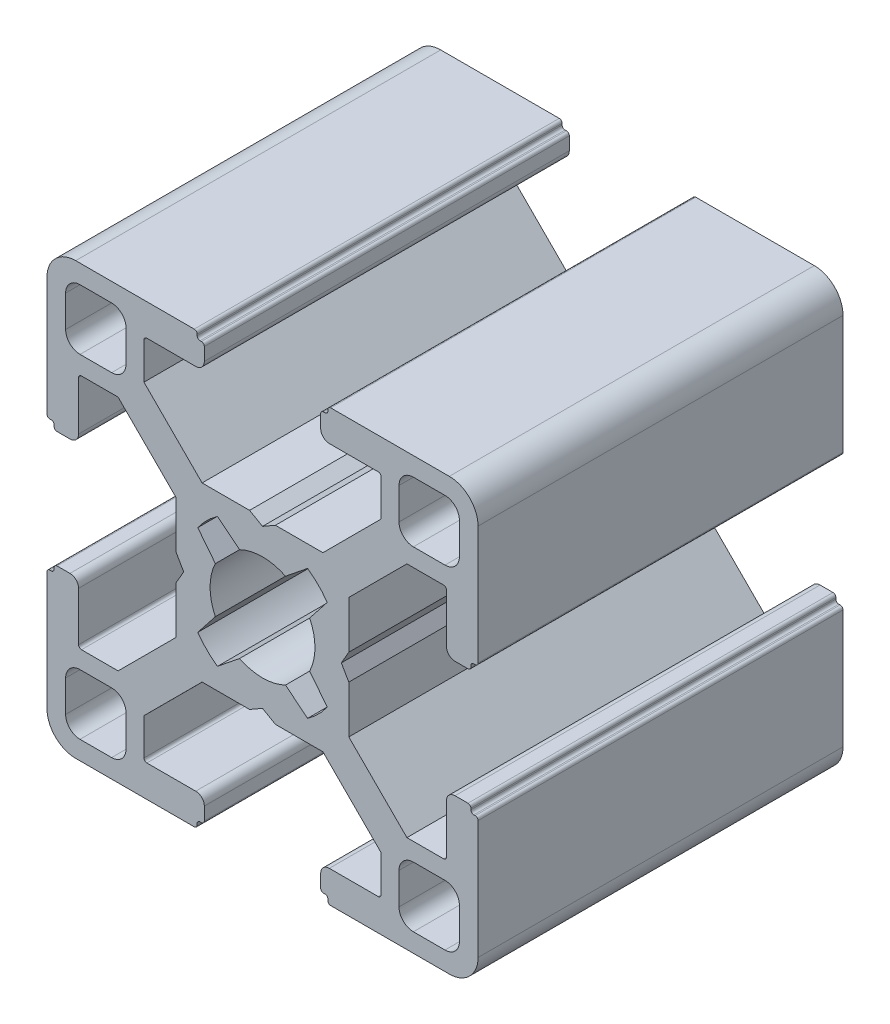
SolidWorks part; units mm, degrees
material "6061 Alloy"
ref_plane "Front" through (0, 0, 0) normal (0, 0, 1) x (1, 0, 0)
ref_plane "Top" through (0, 0, 0) normal (0, 1, 0) x (1, 0, 0)
ref_plane "Right" through (0, 0, 0) normal (1, 0, 0) x (0, 0, -1)
sketch "Sketch1" plane through (0, 0, 0) normal (0, 0, 1) x (1, 0, 0)
  line L0 (13.7, 12.7) -> (13.7, 10.5)
  line L1 (10.5, 9.5) -> (12.7, 9.5)
  line L2 (9.5, 12.7) -> (9.5, 10.5)
  line L3 (10.5, 13.7) -> (12.7, 13.7)
  line L4 (3.1359, 4.5184) -> (1.6001, 3.2806)
  line L5 (3.2806, 1.6001) -> (4.5053, 3.1547)
  line L6 (6.0045, 0.9) -> (5.4849, 0)
  line L7 (6.0045, 4.2045) -> (6.0045, 0.9)
  line L8 (0, -5.4849) -> (0.9, -6)
  line L9 (0.9, -6) -> (4.2045, -6)
  line L10 (4.2045, -6) -> (8.25, -10.05)
  line L11 (8.25, -10.05) -> (8.25, -12.6)
  line L12 (4.65, -12.8) -> (8.05, -12.8)
  line L13 (4.05, -14.3) -> (4.05, -13.4)
  line L14 (4.25, -14.5) -> (4.35, -14.5)
  line L15 (4.55, -14.8) -> (4.55, -14.7)
  line L16 (4.75, -15) -> (13, -15)
  line L17 (15, -13) -> (15, -4.75)
  line L18 (14.7, -4.55) -> (14.8, -4.55)
  line L19 (14.5, -4.35) -> (14.5, -4.25)
  line L20 (13.4, -4.05) -> (14.3, -4.05)
  line L21 (12.8, -8.05) -> (12.8, -4.65)
  line L22 (12.6, -8.25) -> (10.05, -8.25)
  line L23 (10.05, -8.25) -> (6.0045, -4.2045)
  line L24 (6.0045, -4.2045) -> (6.0045, -0.9)
  line L25 (6.0045, -0.9) -> (5.4849, 0)
  line L26 (10.05, 8.25) -> (6.0045, 4.2045)
  line L27 (12.6, 8.25) -> (10.05, 8.25)
  line L28 (12.8, 8.05) -> (12.8, 4.65)
  line L29 (13.4, 4.05) -> (14.3, 4.05)
  line L30 (14.5, 4.35) -> (14.5, 4.25)
  line L31 (14.7, 4.55) -> (14.8, 4.55)
  line L32 (15, 13) -> (15, 4.75)
  line L33 (4.75, 15) -> (13, 15)
  line L34 (4.55, 14.8) -> (4.55, 14.7)
  line L35 (4.25, 14.5) -> (4.35, 14.5)
  line L36 (4.05, 14.3) -> (4.05, 13.4)
  line L37 (4.65, 12.8) -> (8.05, 12.8)
  line L38 (8.25, 10.05) -> (8.25, 12.6)
  line L39 (4.2045, 6) -> (8.25, 10.05)
  line L40 (0.9, 6) -> (4.2045, 6)
  line L41 (0, 5.4849) -> (0.9, 6)
  line L42 (-13.7, -12.7) -> (-13.7, -10.5)
  line L43 (-10.5, -9.5) -> (-12.7, -9.5)
  line L44 (-9.5, -12.7) -> (-9.5, -10.5)
  line L45 (-10.5, -13.7) -> (-12.7, -13.7)
  line L46 (-3.1359, -4.5184) -> (-1.6001, -3.2806)
  line L47 (-3.2806, -1.6001) -> (-4.5053, -3.1547)
  line L48 (0, 5.4849) -> (-0.9, 6)
  line L49 (-0.9, 6) -> (-4.2045, 6)
  line L50 (-4.2045, 6) -> (-8.25, 10.05)
  line L51 (-8.25, 10.05) -> (-8.25, 12.6)
  line L52 (-4.65, 12.8) -> (-8.05, 12.8)
  line L53 (-4.05, 14.3) -> (-4.05, 13.4)
  line L54 (-4.25, 14.5) -> (-4.35, 14.5)
  line L55 (-4.55, 14.8) -> (-4.55, 14.7)
  line L56 (-4.75, 15) -> (-13, 15)
  line L57 (-15, 13) -> (-15, 4.75)
  line L58 (-14.7, 4.55) -> (-14.8, 4.55)
  line L59 (-14.5, 4.35) -> (-14.5, 4.25)
  line L60 (-13.4, 4.05) -> (-14.3, 4.05)
  line L61 (-12.8, 8.05) -> (-12.8, 4.65)
  line L62 (-12.6, 8.25) -> (-10.05, 8.25)
  line L63 (-10.05, 8.25) -> (-6.0045, 4.2045)
  line L64 (-6.0045, -0.9) -> (-5.4849, 0)
  line L65 (-6.0045, -4.2045) -> (-6.0045, -0.9)
  line L66 (-10.05, -8.25) -> (-6.0045, -4.2045)
  line L67 (-12.6, -8.25) -> (-10.05, -8.25)
  line L68 (-12.8, -8.05) -> (-12.8, -4.65)
  line L69 (-13.4, -4.05) -> (-14.3, -4.05)
  line L70 (-14.5, -4.35) -> (-14.5, -4.25)
  line L71 (-14.7, -4.55) -> (-14.8, -4.55)
  line L72 (-15, -13) -> (-15, -4.75)
  line L73 (-4.75, -15) -> (-13, -15)
  line L74 (-4.55, -14.8) -> (-4.55, -14.7)
  line L75 (-4.25, -14.5) -> (-4.35, -14.5)
  line L76 (-4.05, -14.3) -> (-4.05, -13.4)
  line L77 (3.2806, -1.6001) -> (4.5053, -3.1547)
  line L78 (3.1359, -4.5184) -> (1.6001, -3.2806)
  line L79 (-4.65, -12.8) -> (-8.05, -12.8)
  line L80 (-8.25, -10.05) -> (-8.25, -12.6)
  line L81 (-4.2045, -6) -> (-8.25, -10.05)
  line L82 (-0.9, -6) -> (-4.2045, -6)
  line L83 (0, -5.4849) -> (-0.9, -6)
  line L84 (10.5, -13.7) -> (12.7, -13.7)
  line L85 (9.5, -12.7) -> (9.5, -10.5)
  line L86 (10.5, -9.5) -> (12.7, -9.5)
  line L87 (13.7, -12.7) -> (13.7, -10.5)
  line L88 (-6.0045, 4.2045) -> (-6.0045, 0.9)
  line L89 (-6.0045, 0.9) -> (-5.4849, 0)
  line L90 (-3.2806, 1.6001) -> (-4.5053, 3.1547)
  line L91 (-3.1359, 4.5184) -> (-1.6001, 3.2806)
  line L92 (-10.5, 13.7) -> (-12.7, 13.7)
  line L93 (-9.5, 12.7) -> (-9.5, 10.5)
  line L94 (-10.5, 9.5) -> (-12.7, 9.5)
  line L95 (-13.7, 12.7) -> (-13.7, 10.5)
  line L96 (-23.4857, 0) -> (20.9308, 0) construction
  line L97 (0, 17.9563) -> (0, -17.361) construction
  arc A0 (13.7, 12.7) -> (12.7, 13.7) centre (12.7, 12.7) ccw
  arc A1 (12.7, 9.5) -> (13.7, 10.5) centre (12.7, 10.5) ccw
  arc A2 (9.5, 10.5) -> (10.5, 9.5) centre (10.5, 10.5) ccw
  arc A3 (10.5, 13.7) -> (9.5, 12.7) centre (10.5, 12.7) ccw
  arc A4 (1.6001, 3.2806) -> (-1.6001, 3.2806) centre (0, 0) ccw
  arc A5 (8.25, -12.6) -> (8.05, -12.8) centre (8.05, -12.6) cw
  arc A6 (4.65, -12.8) -> (4.05, -13.4) centre (4.65, -13.4) ccw
  arc A7 (4.05, -14.3) -> (4.25, -14.5) centre (4.25, -14.3) ccw
  arc A8 (4.35, -14.5) -> (4.55, -14.7) centre (4.35, -14.7) cw
  arc A9 (4.55, -14.8) -> (4.75, -15) centre (4.75, -14.8) ccw
  arc A10 (13, -15) -> (15, -13) centre (13, -13) ccw
  arc A11 (15, -4.75) -> (14.8, -4.55) centre (14.8, -4.75) ccw
  arc A12 (14.7, -4.55) -> (14.5, -4.35) centre (14.7, -4.35) cw
  arc A13 (14.5, -4.25) -> (14.3, -4.05) centre (14.3, -4.25) ccw
  arc A14 (13.4, -4.05) -> (12.8, -4.65) centre (13.4, -4.65) ccw
  arc A15 (12.8, -8.05) -> (12.6, -8.25) centre (12.6, -8.05) cw
  arc A16 (4.5053, 3.1547) -> (3.1359, 4.5184) centre (0, 0) ccw
  arc A17 (12.8, 8.05) -> (12.6, 8.25) centre (12.6, 8.05) ccw
  arc A18 (13.4, 4.05) -> (12.8, 4.65) centre (13.4, 4.65) cw
  arc A19 (14.5, 4.25) -> (14.3, 4.05) centre (14.3, 4.25) cw
  arc A20 (14.7, 4.55) -> (14.5, 4.35) centre (14.7, 4.35) ccw
  arc A21 (15, 4.75) -> (14.8, 4.55) centre (14.8, 4.75) cw
  arc A22 (13, 15) -> (15, 13) centre (13, 13) cw
  arc A23 (4.55, 14.8) -> (4.75, 15) centre (4.75, 14.8) cw
  arc A24 (4.35, 14.5) -> (4.55, 14.7) centre (4.35, 14.7) ccw
  arc A25 (4.05, 14.3) -> (4.25, 14.5) centre (4.25, 14.3) cw
  arc A26 (4.65, 12.8) -> (4.05, 13.4) centre (4.65, 13.4) cw
  arc A27 (8.25, 12.6) -> (8.05, 12.8) centre (8.05, 12.6) ccw
  arc A28 (-13.7, -12.7) -> (-12.7, -13.7) centre (-12.7, -12.7) ccw
  arc A29 (-12.7, -9.5) -> (-13.7, -10.5) centre (-12.7, -10.5) ccw
  arc A30 (-9.5, -10.5) -> (-10.5, -9.5) centre (-10.5, -10.5) ccw
  arc A31 (-10.5, -13.7) -> (-9.5, -12.7) centre (-10.5, -12.7) ccw
  arc A32 (-4.5053, -3.1547) -> (-3.1359, -4.5184) centre (0, 0) ccw
  arc A33 (-3.2806, 1.6001) -> (-3.2806, -1.6001) centre (0, 0) ccw
  arc A34 (-8.25, 12.6) -> (-8.05, 12.8) centre (-8.05, 12.6) cw
  arc A35 (-4.65, 12.8) -> (-4.05, 13.4) centre (-4.65, 13.4) ccw
  arc A36 (-4.05, 14.3) -> (-4.25, 14.5) centre (-4.25, 14.3) ccw
  arc A37 (-4.35, 14.5) -> (-4.55, 14.7) centre (-4.35, 14.7) cw
  arc A38 (-4.55, 14.8) -> (-4.75, 15) centre (-4.75, 14.8) ccw
  arc A39 (-13, 15) -> (-15, 13) centre (-13, 13) ccw
  arc A40 (-15, 4.75) -> (-14.8, 4.55) centre (-14.8, 4.75) ccw
  arc A41 (-14.7, 4.55) -> (-14.5, 4.35) centre (-14.7, 4.35) cw
  arc A42 (-14.5, 4.25) -> (-14.3, 4.05) centre (-14.3, 4.25) ccw
  arc A43 (-13.4, 4.05) -> (-12.8, 4.65) centre (-13.4, 4.65) ccw
  arc A44 (-12.8, 8.05) -> (-12.6, 8.25) centre (-12.6, 8.05) cw
  arc A45 (-4.5053, 3.1547) -> (-3.1359, 4.5184) centre (0, 0) cw
  arc A46 (-12.8, -8.05) -> (-12.6, -8.25) centre (-12.6, -8.05) ccw
  arc A47 (-13.4, -4.05) -> (-12.8, -4.65) centre (-13.4, -4.65) cw
  arc A48 (-14.5, -4.25) -> (-14.3, -4.05) centre (-14.3, -4.25) cw
  arc A49 (3.2806, 1.6001) -> (3.2806, -1.6001) centre (0, 0) cw
  arc A50 (4.5053, -3.1547) -> (3.1359, -4.5184) centre (0, 0) cw
  arc A51 (1.6001, -3.2806) -> (-1.6001, -3.2806) centre (0, 0) cw
  arc A52 (-14.7, -4.55) -> (-14.5, -4.35) centre (-14.7, -4.35) ccw
  arc A53 (-15, -4.75) -> (-14.8, -4.55) centre (-14.8, -4.75) cw
  arc A54 (-13, -15) -> (-15, -13) centre (-13, -13) cw
  arc A55 (-4.55, -14.8) -> (-4.75, -15) centre (-4.75, -14.8) cw
  arc A56 (10.5, -13.7) -> (9.5, -12.7) centre (10.5, -12.7) cw
  arc A57 (9.5, -10.5) -> (10.5, -9.5) centre (10.5, -10.5) cw
  arc A58 (12.7, -9.5) -> (13.7, -10.5) centre (12.7, -10.5) cw
  arc A59 (13.7, -12.7) -> (12.7, -13.7) centre (12.7, -12.7) cw
  arc A60 (-4.35, -14.5) -> (-4.55, -14.7) centre (-4.35, -14.7) ccw
  arc A61 (-4.05, -14.3) -> (-4.25, -14.5) centre (-4.25, -14.3) cw
  arc A62 (-4.65, -12.8) -> (-4.05, -13.4) centre (-4.65, -13.4) cw
  arc A63 (-8.25, -12.6) -> (-8.05, -12.8) centre (-8.05, -12.6) ccw
  arc A64 (-10.5, 13.7) -> (-9.5, 12.7) centre (-10.5, 12.7) cw
  arc A65 (-9.5, 10.5) -> (-10.5, 9.5) centre (-10.5, 10.5) cw
  arc A66 (-12.7, 9.5) -> (-13.7, 10.5) centre (-12.7, 10.5) cw
  arc A67 (-13.7, 12.7) -> (-12.7, 13.7) centre (-12.7, 12.7) cw
  point P81 (15, 15)
  point P82 (0, 15)
  point P203 (0, -15)
  point P204 (15, -15)
  point P206 (0, 0)
  point P207 (15, 0)
  point P219 (-15, 0)
  point P220 (-15, -15)
  point P221 (-15, 15)
  dimension "D6" = 7.3
  dimension "D7" = 11
  dimension "D1" = 30
  dimension "D2" = 15
  dimension "D3" = 30
  dimension "D4" = 8.1
  dimension "D5" = 9
  dimension "D8" = 8.1
extrude "Boss-Extrude1" add sketch "Sketch1" along normal blind 25.4
